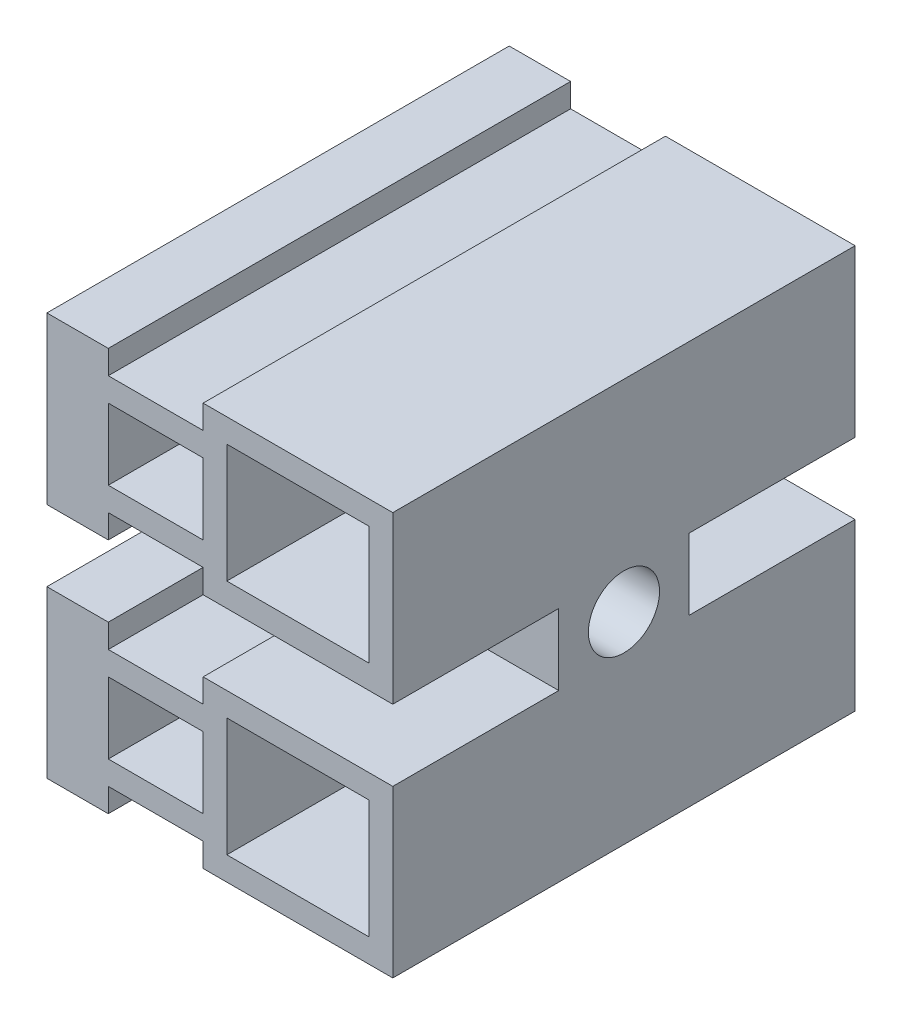
SolidWorks part; units mm, degrees
ref_plane "Alzado" through (0, 0, 0) normal (0, 0, 1) x (1, 0, 0)
ref_plane "Planta" through (0, 0, 0) normal (0, 1, 0) x (1, 0, 0)
ref_plane "Vista lateral" through (0, 0, 0) normal (1, 0, 0) x (0, 0, -1)
sketch "Croquis2" plane through (0, 0, 0) normal (0, 0, 1) x (1, 0, 0)
  line L0 (0, 0) -> (-8, 0)
  line L5 (-8, 0) -> (-8, -1)
  line L6 (-8, -1) -> (-12, -1)
  line L7 (-12, -1) -> (-12, 0)
  line L8 (-12, 0) -> (-14.5893, 0)
  line L9 (-14.5893, 0) -> (-14.5893, -7)
  line L10 (-14.5893, -7) -> (-12, -7)
  line L11 (-12, -7) -> (-12, -6)
  line L12 (-12, -6) -> (-8, -6)
  line L13 (-8, -6) -> (-8, -7)
  line L15 (0, -7) -> (0, 0)
  line L16 (0, -7) -> (0, -10)
  line L17 (-7, -13.5) -> (-8, -13.5) construction
  line L18 (-1, -6) -> (-1, -1)
  line L20 (-1, -1) -> (-7, -1)
  line L21 (-7, -1) -> (-7, -6)
  line L22 (-7, -6) -> (-1, -6)
  line L24 (-1, -3.5) -> (0, -3.5) construction
  line L25 (-4, -1) -> (-4, 0) construction
  line L26 (-7, -3.5) -> (-8, -3.5) construction
  line L27 (-8, -3.5) -> (-8, -2)
  line L28 (-8, -2) -> (-12, -2)
  line L29 (-12, -2) -> (-12, -5)
  line L30 (-12, -5) -> (-8, -5)
  line L31 (-8, -5) -> (-8, -3.5)
  line L32 (-8, -7) -> (-8, -10)
  line L33 (-8, -8.5) -> (0, -8.5)
  line L34 (-4, -16) -> (-4, -17) construction
  line L35 (-1, -13.5) -> (0, -13.5) construction
  line L36 (-8, -12) -> (-8, -13.5)
  line L37 (-12, -12) -> (-8, -12)
  line L38 (-12, -15) -> (-12, -12)
  line L39 (-8, -15) -> (-12, -15)
  line L40 (-8, -13.5) -> (-8, -15)
  line L41 (-7, -11) -> (-1, -11)
  line L42 (-7, -16) -> (-7, -11)
  line L43 (-1, -16) -> (-7, -16)
  line L44 (-1, -11) -> (-1, -16)
  line L45 (0, -10) -> (0, -17)
  line L46 (-8, -11) -> (-8, -10)
  line L47 (-12, -11) -> (-8, -11)
  line L48 (-12, -10) -> (-12, -11)
  line L49 (-14.5893, -10) -> (-12, -10)
  line L50 (-14.5893, -17) -> (-14.5893, -10)
  line L51 (-12, -17) -> (-14.5893, -17)
  line L52 (-12, -16) -> (-12, -17)
  line L53 (-8, -16) -> (-12, -16)
  line L54 (-8, -17) -> (-8, -16)
  line L55 (0, -17) -> (-8, -17)
  dimension "D1" = 8
  dimension "D2" = 4
  dimension "D3" = 4
  dimension "D4" = 8
  dimension "D5" = 1
  dimension "D6" = 7
  dimension "D7" = 1
  dimension "D8" = 1
  dimension "D9" = 5
  dimension "D10" = 1
  dimension "D11" = 1
  dimension "D12" = 4
  dimension "D13" = 1
  dimension "D14" = 6
  dimension "D15" = 1
  dimension "D16" = 1.5
  dimension "D17" = 3
extrude "Saliente-Extruir1" add sketch "Croquis2" along normal blind 19.5 contours L32 L33 L16 L15 L0 L5 L6 L7 L8 L9 L10 L11 L12 L13 L22 L21 L20 L18 L31 L30 L29 L28 L27 | L55 L45 L16 L33 L32 L46 L47 L48 L49 L50 L51 L52 L53 L54 L36 L40 L39 L38 L37 L41 L44 L43 L42
sketch "Croquis4" plane through (-8, 0, 0) normal (-1, 0, 0) x (0, 0, 1)
  line L0 (9.75, -6) -> (9.75, -7) construction
  line L1 (19.5, -6) -> (0, -6) construction
  line L2 (9.75, -11) -> (9.75, -10) construction
  line L3 (19.5, -11) -> (0, -11) construction
  line L4 (0, -6) -> (0, -11) construction
  line L6 (0, -7) -> (0, -10)
  line L8 (19.5, -7) -> (19.5, -10)
  line L9 (19.5, -6) -> (19.5, -11) construction
  line L10 (19.5, -8.5) -> (12.5, -8.5) construction
  line L11 (0, -8.5) -> (7, -8.5) construction
  line L12 (7, -7) -> (0, -7)
  line L13 (7, -7) -> (12.5, -7) construction
  line L14 (7, -7) -> (7, -10)
  line L15 (7, -10) -> (12.5, -10) construction
  line L16 (12.5, -7) -> (12.5, -10)
  line L17 (12.5, -7) -> (19.5, -7)
  line L18 (12.5, -10) -> (19.5, -10)
  line L19 (7, -10) -> (0, -10)
  circle A0 centre (9.75, -8.5) radius 1.5
  dimension "D1" = 1
  dimension "D2" = 1
  dimension "D3" = 7
  dimension "D4" = 7
extrude "Cortar-Extruir1" cut sketch "Croquis4" against normal up to next
